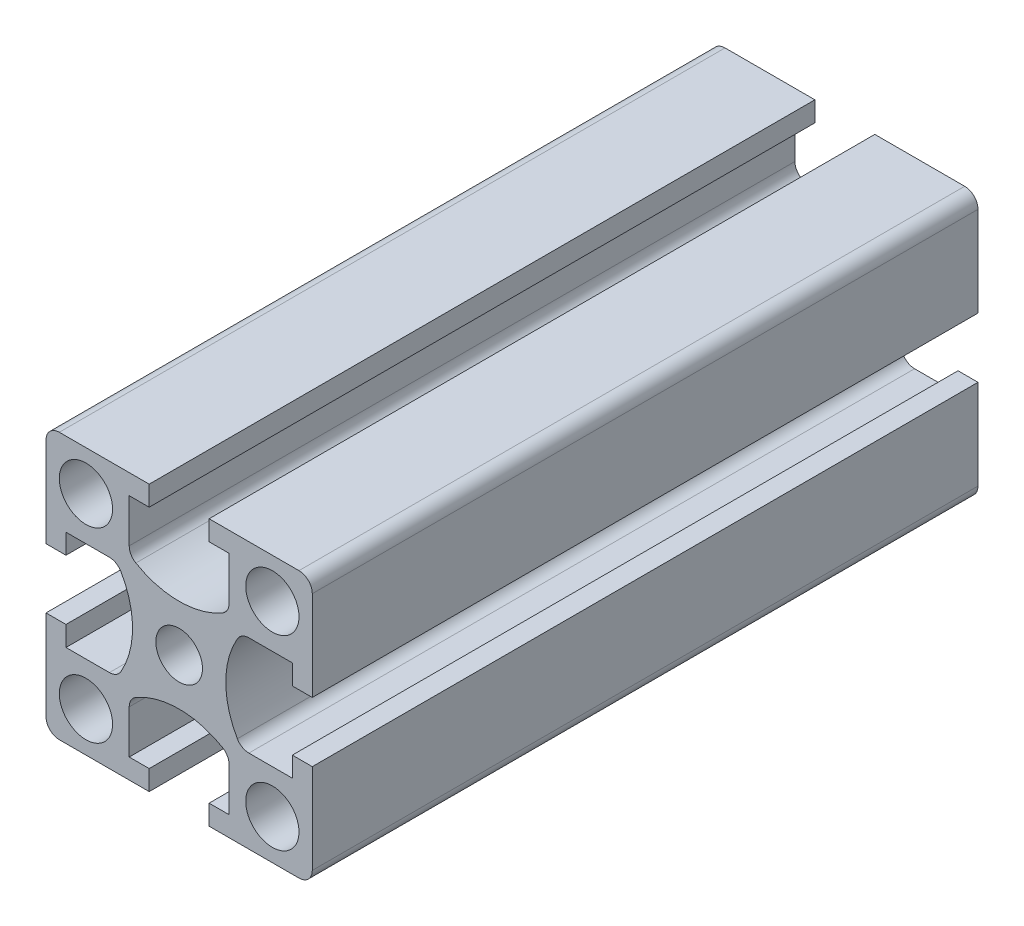
SolidWorks part; units mm, degrees
ref_plane "Front Plane" through (0, 0, 0) normal (0, 0, 1) x (1, 0, 0)
ref_plane "Top Plane" through (0, 0, 0) normal (0, 1, 0) x (1, 0, 0)
ref_plane "Right Plane" through (0, 0, 0) normal (1, 0, 0) x (0, 0, -1)
sketch "Sketch1" plane through (0, 0, 0) normal (0, 0, 1) x (1, 0, 0)
  line L64 (-20, 18) -> (-20, 4.5)
  line L65 (-20, 4.5) -> (-17, 4.5)
  line L66 (-17, 4.5) -> (-17, 7.5)
  line L67 (-17, 7.5) -> (-10.4737, 7.5)
  line L68 (-10.4737, -7.5) -> (-17, -7.5)
  line L69 (-17, -7.5) -> (-17, -4.5)
  line L70 (-17, -4.5) -> (-20, -4.5)
  line L71 (-20, -4.5) -> (-20, -18)
  line L72 (-18, -20) -> (-4.5, -20)
  line L73 (-4.5, -20) -> (-4.5, -17)
  line L74 (-4.5, -17) -> (-7.5, -17)
  line L75 (-7.5, -17) -> (-7.5, -10.4737)
  line L76 (7.5, -10.4737) -> (7.5, -17)
  line L77 (7.5, -17) -> (4.5, -17)
  line L78 (4.5, -17) -> (4.5, -20)
  line L79 (4.5, -20) -> (18, -20)
  line L80 (20, -18) -> (20, -4.5)
  line L81 (20, -4.5) -> (17, -4.5)
  line L82 (17, -4.5) -> (17, -7.5)
  line L83 (17, -7.5) -> (10.4737, -7.5)
  line L84 (10.4737, 7.5) -> (17, 7.5)
  line L85 (17, 7.5) -> (17, 4.5)
  line L86 (17, 4.5) -> (20, 4.5)
  line L87 (20, 4.5) -> (20, 18)
  line L88 (18, 20) -> (4.5, 20)
  line L89 (4.5, 20) -> (4.5, 17)
  line L90 (4.5, 17) -> (7.5, 17)
  line L91 (7.5, 17) -> (7.5, 10.4737)
  line L92 (-7.5, 10.4737) -> (-7.5, 17)
  line L93 (-7.5, 17) -> (-4.5, 17)
  line L94 (-4.5, 17) -> (-4.5, 20)
  line L95 (-4.5, 20) -> (-18, 20)
  circle A5 centre (-14, -14) radius 4
  circle A6 centre (14, -14) radius 4
  circle A7 centre (14, 14) radius 4
  circle A8 centre (0, 0) radius 3.5
  circle A9 centre (-14, 14) radius 4
  arc A32 (-18, 20) -> (-20, 18) centre (-18, 18) ccw
  arc A33 (-8.7417, 6.5) -> (-10.4737, 7.5) centre (-10.4737, 5.5) ccw
  arc A34 (-8.7417, -6.5) -> (-8.7417, 6.5) centre (-20, 0) ccw
  arc A35 (-10.4737, -7.5) -> (-8.7417, -6.5) centre (-10.4737, -5.5) ccw
  arc A36 (-20, -18) -> (-18, -20) centre (-18, -18) ccw
  arc A37 (-6.5, -8.7417) -> (-7.5, -10.4737) centre (-5.5, -10.4737) ccw
  arc A38 (6.5, -8.7417) -> (-6.5, -8.7417) centre (0, -20) ccw
  arc A39 (7.5, -10.4737) -> (6.5, -8.7417) centre (5.5, -10.4737) ccw
  arc A40 (18, -20) -> (20, -18) centre (18, -18) ccw
  arc A41 (8.7417, -6.5) -> (10.4737, -7.5) centre (10.4737, -5.5) ccw
  arc A42 (8.7417, 6.5) -> (8.7417, -6.5) centre (20, 0) ccw
  arc A43 (10.4737, 7.5) -> (8.7417, 6.5) centre (10.4737, 5.5) ccw
  arc A44 (20, 18) -> (18, 20) centre (18, 18) ccw
  arc A45 (6.5, 8.7417) -> (7.5, 10.4737) centre (5.5, 10.4737) ccw
  arc A46 (-6.5, 8.7417) -> (6.5, 8.7417) centre (0, 20) ccw
  arc A47 (-7.5, 10.4737) -> (-6.5, 8.7417) centre (-5.5, 10.4737) ccw
extrude "Boss-Extrude1" add sketch "Sketch1" along normal blind 100
